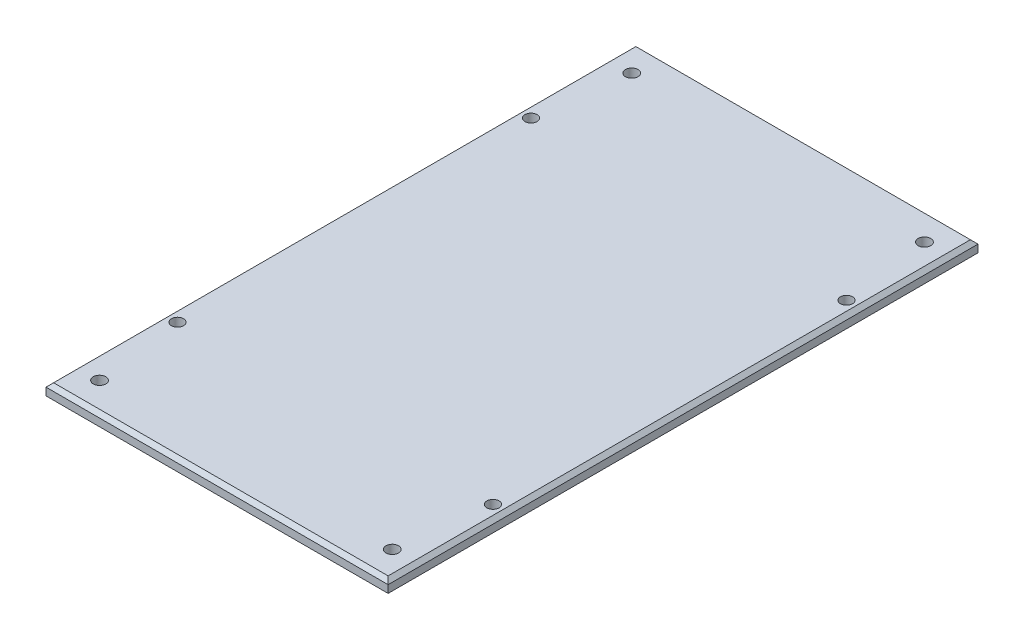
SolidWorks part; units mm, degrees
ref_plane "Front Plane" through (0, 0, 0) normal (0, 0, 1) x (1, 0, 0)
ref_plane "Top Plane" through (0, 0, 0) normal (0, 1, 0) x (1, 0, 0)
ref_plane "Right Plane" through (0, 0, 0) normal (1, 0, 0) x (0, 0, -1)
sketch "Sketch1" plane through (0, 0, 0) normal (0, 1, 0) x (1, 0, 0)
  line L0 (-45, 77.5862) -> (-45, -77.5862)
  line L1 (-45, -77.5862) -> (45, -77.5862)
  line L2 (45, -77.5862) -> (45, 77.5862)
  line L3 (45, 77.5862) -> (-45, 77.5862)
  circle A0 centre (38.5, -70) radius 1.6552
  circle A1 centre (-38.5, -70) radius 1.6552
  circle A2 centre (38.5, 70) radius 1.6552
  circle A3 centre (-38.5, 70) radius 1.6552
  point P12 (0, 77.5862)
  point P14 (45, 0)
  point P15 (0, 0)
  point P16 (0, 0)
  point P17 (0, 0)
  point P18 (0, 0)
  point P19 (0, 0)
  dimension "D3" = 77
  dimension "D4" = 140
  dimension "D5" = 70
  dimension "D6" = 38.5
  dimension "D1" = 45
  dimension "D2" = 45
extrude "Boss-Extrude1" add sketch "Sketch1" along normal blind 3
sketch "Sketch2" plane through (0, 3, 0) normal (0, 1, 0) x (1, 0, 0)
  line L5 (-41.5, -46.5) -> (41.5, -46.5)
  line L6 (-41.5, -46.5) -> (-41.5, 46.5)
  line L7 (-41.5, 46.5) -> (41.5, 46.5)
  line L8 (41.5, -46.5) -> (41.5, 46.5)
  line L9 (-41.5, -46.5) -> (41.5, 46.5) construction
  line L10 (-41.5, 46.5) -> (41.5, -46.5) construction
  circle A0 centre (-41.5, 46.5) radius 1.6
  circle A1 centre (41.5, 46.5) radius 1.6
  circle A3 centre (-41.5, -46.5) radius 1.6
  circle A4 centre (41.5, -46.5) radius 1.6
  point P0 (0, 0)
  dimension "D3" = 3.2
  dimension "D1" = 93
  dimension "D2" = 83
extrude "Cut-Extrude1" cut sketch "Sketch2" against normal through all contours L7 A0 L6 | L6 A0 L7 | L7 A1 L8 | L8 A1 L7 | L8 A4 L5 | L5 A4 L8 | L6 A3 L5 | L5 A3 L6
sketch "Sketch5" plane through (0, 3, 0) normal (0, 1, 0) x (1, 0, 0)
  circle A0 centre (-38.5, 70) radius 3
  circle A1 centre (38.5, 70) radius 3
  circle A2 centre (38.5, -70) radius 3
  circle A3 centre (-38.5, -70) radius 3
  dimension "D1" = 6
chamfer "Chamfer1" distance 1 angle 45 2 edges at (0, 3, 77.5862) (0, 3, -77.5862)
chamfer "Chamfer2" distance 1 angle 45 2 edges at (45, 3, 0) (-45, 3, 0)
